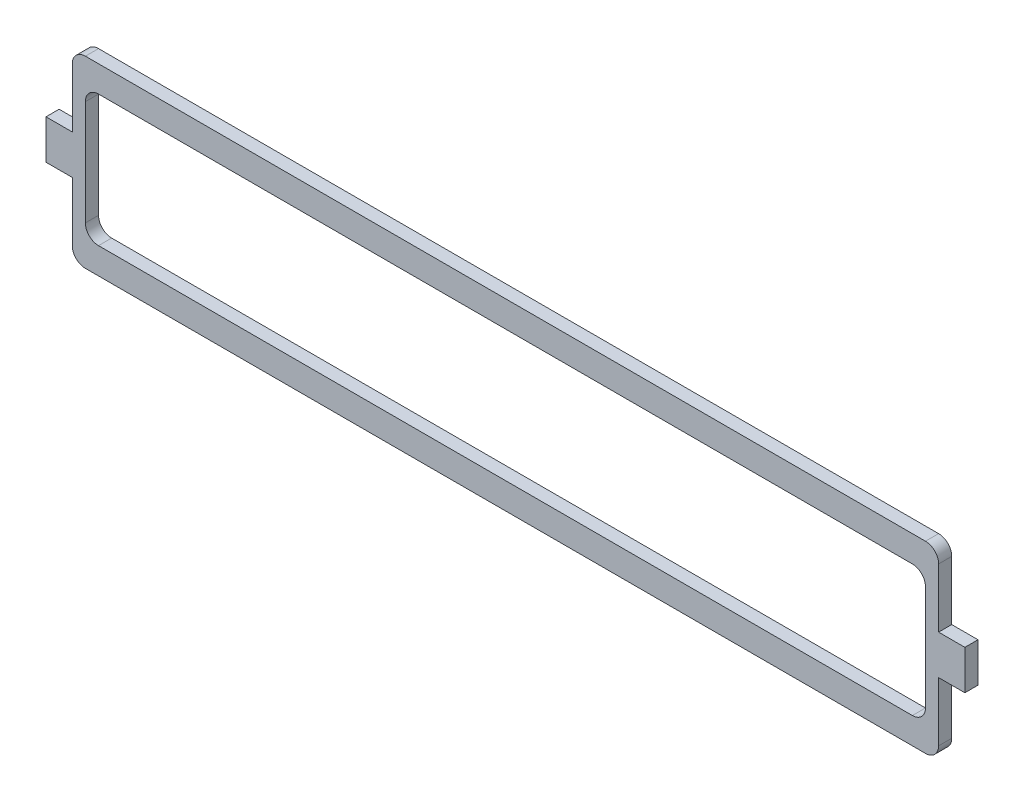
SolidWorks part; units mm, degrees
ref_plane "Front Plane" through (0, 0, 0) normal (0, 0, 1) x (1, 0, 0)
ref_plane "Top Plane" through (0, 0, 0) normal (0, 1, 0) x (1, 0, 0)
ref_plane "Right Plane" through (0, 0, 0) normal (1, 0, 0) x (0, 0, -1)
sketch "Sketch1" plane through (0, 0, 0) normal (0, 0, 1) x (1, 0, 0)
  line L0 (-90.218, 7.5) -> (299.3045, 7.5) construction
  line L1 (-75.8133, 35) -> (254.1867, 35)
  line L3 (-75.8133, -35) -> (254.1867, -35)
  line L5 (-85.8133, -7.5) -> (-75.8133, -7.5)
  line L6 (-91.3268, 0) -> (299.3045, 0) construction
  line L9 (-85.8133, 7.5) -> (-75.8133, 7.5)
  line L10 (-75.8133, 17.5) -> (-75.8133, 7.5)
  line L11 (-75.8133, -17.5) -> (-75.8133, -7.5)
  line L14 (89.1867, 30.0157) -> (89.1867, -45.8134) construction
  line L15 (-78.3133, 24.0051) -> (-78.3133, -32.23) construction
  line L18 (254.1867, -17.5) -> (254.1867, -7.5)
  line L19 (264.1867, -7.5) -> (254.1867, -7.5)
  line L20 (264.1867, 7.5) -> (254.1867, 7.5)
  line L21 (254.1867, 17.5) -> (254.1867, 7.5)
  line L24 (264.1867, 7.5) -> (264.1867, -7.5)
  line L25 (254.1867, 17.5) -> (254.1867, 35)
  line L26 (254.1867, -17.5) -> (254.1867, -35)
  line L27 (-75.8133, 17.5) -> (-75.8133, 35)
  line L28 (-85.8133, 7.5) -> (-85.8133, -7.5)
  line L29 (-75.8133, -17.5) -> (-75.8133, -35)
  point P6 (89.1867, -35)
  dimension "D5" = 330
  dimension "D1" = 70
  dimension "D2" = 10
  dimension "D3" = 15
  dimension "D4" = 10
extrude "Boss-Extrude1" add sketch "Sketch1" along normal blind 5
sketch "Esquisse1" plane through (0, 0, 5) normal (0, 0, 1) x (1, 0, 0)
  line L0 (254.1867, 35) -> (-75.8133, 35) construction
  line L1 (-70.8133, 25) -> (249.1867, 25)
  line L2 (-70.8133, 25) -> (-70.8133, -25)
  line L3 (-70.8133, -25) -> (249.1867, -25)
  line L4 (249.1867, 25) -> (249.1867, -25)
  line L5 (-75.8133, -35) -> (254.1867, -35) construction
  line L6 (-75.8133, 7.5) -> (-75.8133, 35) construction
  line L7 (254.1867, 35) -> (254.1867, 7.5) construction
  dimension "D1" = 10
  dimension "D2" = 10
  dimension "D3" = 5
  dimension "D4" = 5
extrude "Enlèv. mat.-Extru.1" cut sketch "Esquisse1" against normal blind 10
fillet "Congé1" radius 5 8 edges at (249.1867, -25, 2.5) (-70.8133, -25, 2.5) (-70.8133, 25, 2.5) (249.1867, 25, 2.5) (254.1867, 35, 2.5) (254.1867, -35, 2.5) (-75.8133, -35, 2.5) (-75.8133, 35, 2.5)
